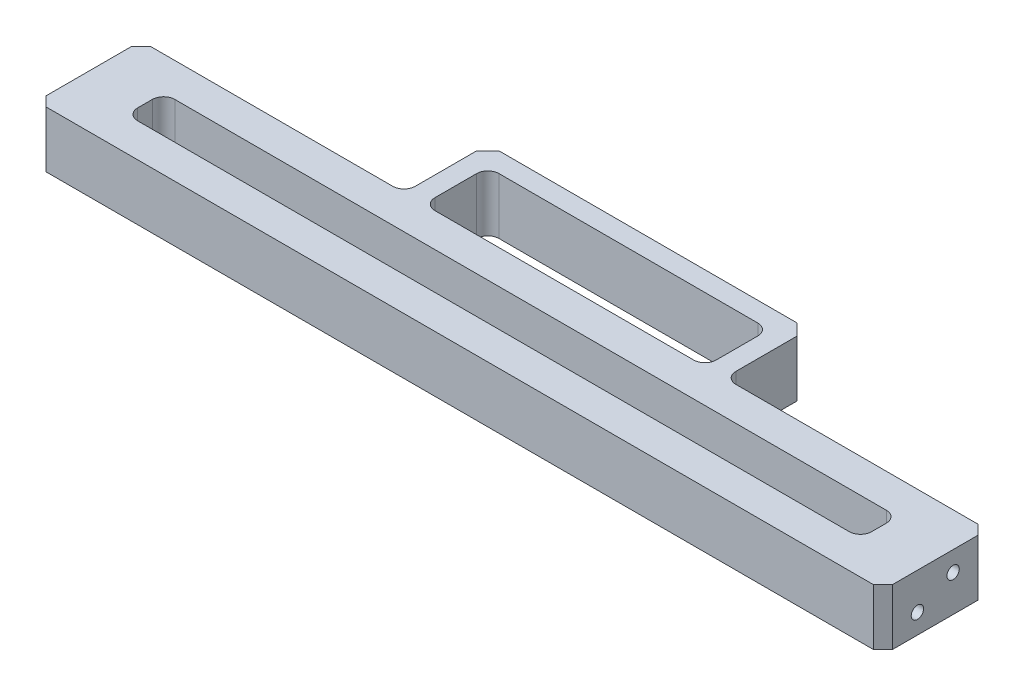
SolidWorks part; units mm, degrees
material "PLA2"
ref_plane "Front Plane" through (0, 0, 0) normal (0, 0, 1) x (1, 0, 0)
ref_plane "Top Plane" through (0, 0, 0) normal (0, 1, 0) x (1, 0, 0)
ref_plane "Right Plane" through (0, 0, 0) normal (1, 0, 0) x (0, 0, -1)
sketch "Sketch2" plane through (0, 0, 0) normal (0, 1, 0) x (1, 0, 0)
  line L0 (95.5675, 11.811) -> (-95.5675, 11.811)
  line L1 (-95.5675, 11.811) -> (-95.5675, -11.811)
  line L2 (-95.5675, -11.811) -> (95.5675, -11.811)
  line L3 (0, 11.811) -> (0, -11.811) construction
  line L4 (95.5675, 11.811) -> (95.5675, -11.811)
  line L5 (-95.5675, 11.811) -> (-101.2825, 11.811) construction
  line L6 (-101.2825, 11.811) -> (-101.2825, -11.811) construction
  line L7 (-101.2825, -11.811) -> (-95.5675, -11.811) construction
  line L8 (95.5675, 11.811) -> (101.2825, 11.811) construction
  line L9 (101.2825, -11.811) -> (95.5675, -11.811) construction
  line L10 (101.2825, 11.811) -> (101.2825, -11.811) construction
  point P8 (0, 11.811)
  dimension "D1" = 23.622
  dimension "D2" = 5.715
  dimension "D3" = 202.565
extrude "Mount-Bar" add sketch "Sketch2" along normal mid plane 12.7
sketch "Sketch4" plane through (0, 6.35, 0) normal (0, 1, 0) x (1, 0, 0)
  line L0 (0, 0) -> (0, 11.811) construction
  line L1 (95.5675, 11.811) -> (-95.5675, 11.811) construction
  line L2 (-31.75, 11.811) -> (-31.75, 26.289)
  line L3 (-31.75, 26.289) -> (31.75, 26.289)
  line L4 (-31.75, 11.811) -> (-36.195, 11.811)
  line L5 (-36.195, 11.811) -> (-36.195, 30.734)
  line L6 (-36.195, 30.734) -> (36.195, 30.734)
  line L7 (36.195, 11.811) -> (36.195, 30.734)
  line L8 (31.75, 11.811) -> (36.195, 11.811)
  line L9 (31.75, 11.811) -> (31.75, 26.289)
  line L10 (-95.5675, -11.811) -> (95.5675, -11.811) construction
  point P12 (0, 30.734)
  point P15 (0, 26.289)
  dimension "D1" = 63.5
  dimension "D2" = 4.445
  dimension "D3" = 4.445
  dimension "D4" = 38.1
extrude "Mount-Feature" add sketch "Sketch4" against normal up to surface (12.7 mm away) up to face at (0, -6.35, 0)
fillet "Fillet1" radius 2.54 6 edges at (-31.75, 0, -11.811) (31.75, 0, -11.811) (31.75, 0, -26.289) (-31.75, 0, -26.289) (36.195, 0, -11.811) (-36.195, 0, -11.811)
sketch "Sketch5" plane through (-95.5675, 0, 0) normal (-1, 0, 0) x (0, 0, 1)
  line L0 (0, 0) -> (32139.3805, -38302.2222) construction
  line L1 (-11.811, -6.35) -> (11.811, -6.35) construction
  line L2 (0, 0) -> (38302.2222, 32139.3805) construction
  line L3 (19.9667, -13.9165) -> (-10.2379, 22.0799) construction
  line L4 (-10.2379, 22.0799) -> (-19.9667, 13.9165) construction
  line L5 (10.2379, -22.0799) -> (-19.9667, 13.9165) construction
  line L6 (19.9667, -13.9165) -> (10.2379, -22.0799) construction
  line L7 (0, 0) -> (-4.0285, 1.8785) construction
  line L8 (0, 0) -> (4.0285, -1.8785) construction
  circle A0 centre (-12.2451, 14.5931) radius 1.5875 construction
  circle A1 centre (12.2451, -14.5931) radius 1.5875 construction
  circle A2 centre (-4.0285, 1.8785) radius 1.397
  circle A3 centre (4.0285, -1.8785) radius 1.397
  point P7 (15.1023, -17.9982)
  point P11 (-15.1023, 17.9982)
  point P13 (-4.8644, -4.0817)
  point P14 (4.8644, 4.0817)
  dimension "D4" = 3.175
  dimension "D6" = 2.794
  dimension "D7" = 2.794
  dimension "D1" = 50
  dimension "D2" = 12.7
  dimension "D3" = 38.1
  dimension "D5" = 46.99
  dimension "D8" = 25
  dimension "D10" = 4.445
  dimension "D11" = 25
  dimension "0.175" = 4.445
extrude "Mount-Holes" cut sketch "Sketch5" against normal blind 10.795
mirror "Mirror1" about plane through (0, 0, 0) normal (1, 0, 0) of "Mount-Holes"
sketch "Sketch6" plane through (0, -6.35, 0) normal (0, -1, 0) x (1, 0, 0)
  line L0 (-26.67, -11.811) -> (-26.67, -4.826)
  line L1 (29.21, -11.811) -> (-29.21, -11.811) construction
  line L2 (-26.67, -4.826) -> (26.67, -4.826)
  line L3 (-26.67, -11.811) -> (26.67, -11.811)
  line L4 (0, 0) -> (0, -11.811) construction
  line L5 (26.67, -11.811) -> (26.67, -4.826)
  point P10 (0, -4.826)
  dimension "D1" = 6.985
  dimension "D2" = 53.34
extrude "Boss-Extrude5" add sketch "Sketch6" along normal blind 12.7
fillet "Fillet2" radius 2.54 3 edges at (-26.67, -6.35, -8.3185) (0, -6.35, -4.826) (26.67, -6.35, -8.3185)
chamfer "Chamfer1" distance 2.54 angle 45 3 edges at (-36.195, 0, -30.734) (36.195, 0, -30.734) (0, -19.05, -4.826)
chamfer "Chamfer2" distance 2.159 angle 45 4 edges at (-95.5675, 0, 11.811) (-95.5675, 0, -11.811) (95.5675, 0, 11.811) (95.5675, 0, -11.811)
sketch "Sketch7" plane through (0, 6.35, 0) normal (0, 1, 0) x (1, 0, 0)
  line L0 (0, 0) -> (0, -11.811) construction
  line L1 (-93.4085, -11.811) -> (93.4085, -11.811) construction
  line L2 (82.8675, 4.191) -> (-82.8675, 4.191)
  line L3 (-82.8675, 4.191) -> (-82.8675, -4.191)
  line L4 (82.8675, 4.191) -> (82.8675, -4.191)
  line L5 (-96.8375, 0) -> (49903.1625, 0) construction
  line L6 (-95.5675, 9.652) -> (-95.5675, -9.652) construction
  line L7 (95.5675, -9.652) -> (95.5675, 9.652) construction
  line L8 (82.8675, -4.191) -> (-82.8675, -4.191)
  point P8 (0, -4.191)
  point P10 (0, 4.191)
  point P14 (-95.5675, 0)
  point P17 (95.5675, 0)
  point P19 (82.8675, 0)
  point P20 (-82.8675, 0)
  dimension "D1" = 7.62
  dimension "D2" = 12.7
extrude "weight-reduction" cut sketch "Sketch7" against normal through all
fillet "Fillet3" radius 2.54 4 edges at (-82.8675, 0, -4.191) (-82.8675, 0, 4.191) (82.8675, 0, 4.191) (82.8675, 0, -4.191)
